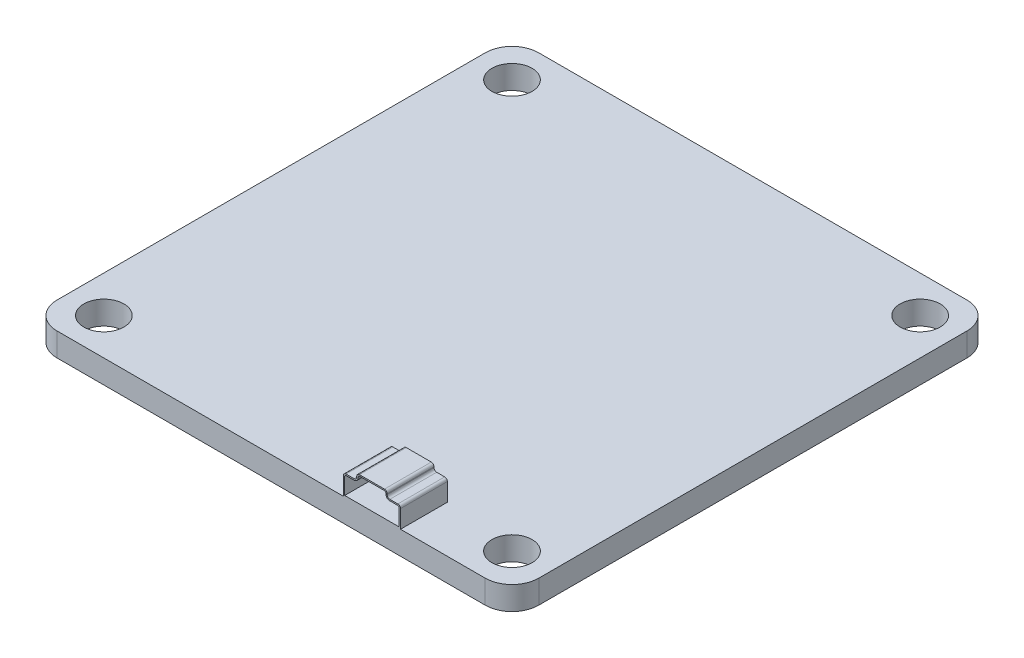
SolidWorks part; units mm, degrees
ref_plane "Front Plane" through (0, 0, 0) normal (0, 0, 1) x (1, 0, 0)
ref_plane "Top Plane" through (0, 0, 0) normal (0, 1, 0) x (1, 0, 0)
ref_plane "Right Plane" through (0, 0, 0) normal (1, 0, 0) x (0, 0, -1)
sketch "Sketch1" plane through (0, 0, 0) normal (0, 1, 0) x (1, 0, 0)
  line L1 (-16, 18) -> (16, 18)
  line L2 (-18, 16) -> (-18, -16)
  line L3 (-16, -18) -> (16, -18)
  line L4 (18, 16) -> (18, -16)
  line L5 (-18, 18) -> (18, -18) construction
  line L6 (-18, -18) -> (18, 18) construction
  line L7 (-15.25, 15.25) -> (15.25, 15.25) construction
  line L8 (-15.25, 15.25) -> (-15.25, -15.25) construction
  line L9 (-15.25, -15.25) -> (15.25, -15.25) construction
  line L10 (15.25, 15.25) -> (15.25, -15.25) construction
  line L11 (-15.25, 15.25) -> (15.25, -15.25) construction
  line L12 (-15.25, -15.25) -> (15.25, 15.25) construction
  circle A0 centre (-15.25, 15.25) radius 1.5
  circle A1 centre (15.25, 15.25) radius 1.5
  circle A2 centre (15.25, -15.25) radius 1.5
  circle A3 centre (-15.25, -15.25) radius 1.5
  arc A4 (-18, -16) -> (-16, -18) centre (-16, -16) ccw
  arc A5 (16, -18) -> (18, -16) centre (16, -16) ccw
  arc A6 (16, 18) -> (18, 16) centre (16, 16) cw
  arc A7 (-16, 18) -> (-18, 16) centre (-16, 16) ccw
  point P0 (0, 0)
  point P6 (0, 0)
  dimension "D5" = 3
  dimension "D6" = 2
  dimension "D1" = 36
  dimension "D2" = 36
  dimension "D3" = 30.5
  dimension "D4" = 30.5
extrude "Boss-Extrude1" add sketch "Sketch1" along normal blind 1.75
sketch "Sketch2" plane through (0, 0, 18) normal (0, 0, 1) x (1, 0, 0)
  line L0 (-16, 1.75) -> (16, 1.75) construction
  line L1 (5.3983, 1.75) -> (9.6704, 1.75)
  line L2 (5.3983, 1.75) -> (5.3983, 3.0895)
  line L3 (6.5983, 3.75) -> (8.4704, 3.75)
  line L4 (9.6704, 1.75) -> (9.6704, 3.0895)
  line L5 (6.3983, 3.55) -> (6.3983, 3.4895)
  line L6 (6.1983, 3.2895) -> (5.5983, 3.2895)
  line L7 (8.6704, 3.55) -> (8.6704, 3.4895)
  line L8 (8.8704, 3.2895) -> (9.4704, 3.2895)
  line L9 (6.5983, 3.65) -> (8.4704, 3.65)
  line L10 (8.5704, 3.55) -> (8.5704, 3.4895)
  line L11 (8.8704, 3.1895) -> (9.4704, 3.1895)
  line L12 (9.5704, 1.85) -> (9.5704, 3.0895)
  line L13 (5.4983, 1.85) -> (9.5704, 1.85)
  line L14 (5.4983, 1.85) -> (5.4983, 3.0895)
  line L15 (6.1983, 3.1895) -> (5.5983, 3.1895)
  line L16 (6.4983, 3.55) -> (6.4983, 3.4895)
  arc A0 (9.4704, 3.2895) -> (9.6704, 3.0895) centre (9.4704, 3.0895) cw
  arc A1 (8.6704, 3.4895) -> (8.8704, 3.2895) centre (8.8704, 3.4895) ccw
  arc A2 (8.6704, 3.55) -> (8.4704, 3.75) centre (8.4704, 3.55) ccw
  arc A3 (6.3983, 3.55) -> (6.5983, 3.75) centre (6.5983, 3.55) cw
  arc A4 (6.3983, 3.4895) -> (6.1983, 3.2895) centre (6.1983, 3.4895) cw
  arc A5 (5.5983, 3.2895) -> (5.3983, 3.0895) centre (5.5983, 3.0895) ccw
  arc A6 (8.5704, 3.55) -> (8.4704, 3.65) centre (8.4704, 3.55) ccw
  arc A7 (8.5704, 3.4895) -> (8.8704, 3.1895) centre (8.8704, 3.4895) ccw
  arc A8 (9.4704, 3.1895) -> (9.5704, 3.0895) centre (9.4704, 3.0895) cw
  arc A9 (5.5983, 3.1895) -> (5.4983, 3.0895) centre (5.5983, 3.0895) ccw
  arc A10 (6.4983, 3.4895) -> (6.1983, 3.1895) centre (6.1983, 3.4895) cw
  arc A11 (6.4983, 3.55) -> (6.5983, 3.65) centre (6.5983, 3.55) cw
  point P11 (9.6704, 3.2895)
  point P15 (8.6704, 3.2895)
  point P22 (6.3983, 3.2895)
  point P25 (5.3983, 3.2895)
  dimension "D3" = 0.2
  dimension "D1" = 1
  dimension "D2" = 1
  dimension "D4" = 0.1
extrude "Boss-Extrude2" add sketch "Sketch2" against normal blind 3
sketch "Sketch4" plane through (0, 0, 15) normal (0, 0, -1) x (-1, 0, 0)
  line L8 (-5.3983, 1.75) -> (-5.3983, 3.0895)
  line L9 (-5.5983, 3.2895) -> (-6.1983, 3.2895)
  line L10 (-6.3983, 3.4895) -> (-6.3983, 3.55)
  line L11 (-6.5983, 3.75) -> (-8.4704, 3.75)
  line L12 (-8.6704, 3.55) -> (-8.6704, 3.4895)
  line L13 (-8.8704, 3.2895) -> (-9.4704, 3.2895)
  line L14 (-9.6704, 3.0895) -> (-9.6704, 1.75)
  line L15 (-9.6704, 1.75) -> (-5.3983, 1.75)
  line L16 (-5.3983, 1.75) -> (-5.3983, 3.0895)
  line L17 (-5.5983, 3.2895) -> (-6.1983, 3.2895)
  line L18 (-6.3983, 3.4895) -> (-6.3983, 3.55)
  line L19 (-6.5983, 3.75) -> (-8.4704, 3.75)
  line L20 (-8.6704, 3.55) -> (-8.6704, 3.4895)
  line L21 (-8.8704, 3.2895) -> (-9.4704, 3.2895)
  line L22 (-9.6704, 3.0895) -> (-9.6704, 1.75)
  line L23 (-9.6704, 1.75) -> (-5.3983, 1.75)
  arc A6 (-5.3983, 3.0895) -> (-5.5983, 3.2895) centre (-5.5983, 3.0895) ccw
  arc A7 (-6.3983, 3.4895) -> (-6.1983, 3.2895) centre (-6.1983, 3.4895) ccw
  arc A8 (-6.3983, 3.55) -> (-6.5983, 3.75) centre (-6.5983, 3.55) ccw
  arc A9 (-8.4704, 3.75) -> (-8.6704, 3.55) centre (-8.4704, 3.55) ccw
  arc A10 (-8.8704, 3.2895) -> (-8.6704, 3.4895) centre (-8.8704, 3.4895) ccw
  arc A11 (-9.4704, 3.2895) -> (-9.6704, 3.0895) centre (-9.4704, 3.0895) ccw
  arc A12 (-5.3983, 3.0895) -> (-5.5983, 3.2895) centre (-5.5983, 3.0895) ccw
  arc A13 (-6.3983, 3.4895) -> (-6.1983, 3.2895) centre (-6.1983, 3.4895) ccw
  arc A14 (-6.3983, 3.55) -> (-6.5983, 3.75) centre (-6.5983, 3.55) ccw
  arc A15 (-8.4704, 3.75) -> (-8.6704, 3.55) centre (-8.4704, 3.55) ccw
  arc A16 (-8.8704, 3.2895) -> (-8.6704, 3.4895) centre (-8.8704, 3.4895) ccw
  arc A17 (-9.4704, 3.2895) -> (-9.6704, 3.0895) centre (-9.4704, 3.0895) ccw
  dimension "D1" = 0
extrude "Boss-Extrude3" add sketch "Sketch4" along normal blind 0.5
sketch "Sketch6" plane through (0, 0, 14.5) normal (0, 0, -1) x (-1, 0, 0)
  circle A0 centre (-7.5882, 2.8452) radius 0.2579
  circle A1 centre (-8.2587, 2.8452) radius 0.2579
  circle A2 centre (-6.9539, 2.8452) radius 0.2579
extrude "Cut-Extrude1" cut sketch "Sketch6" against normal up to next
